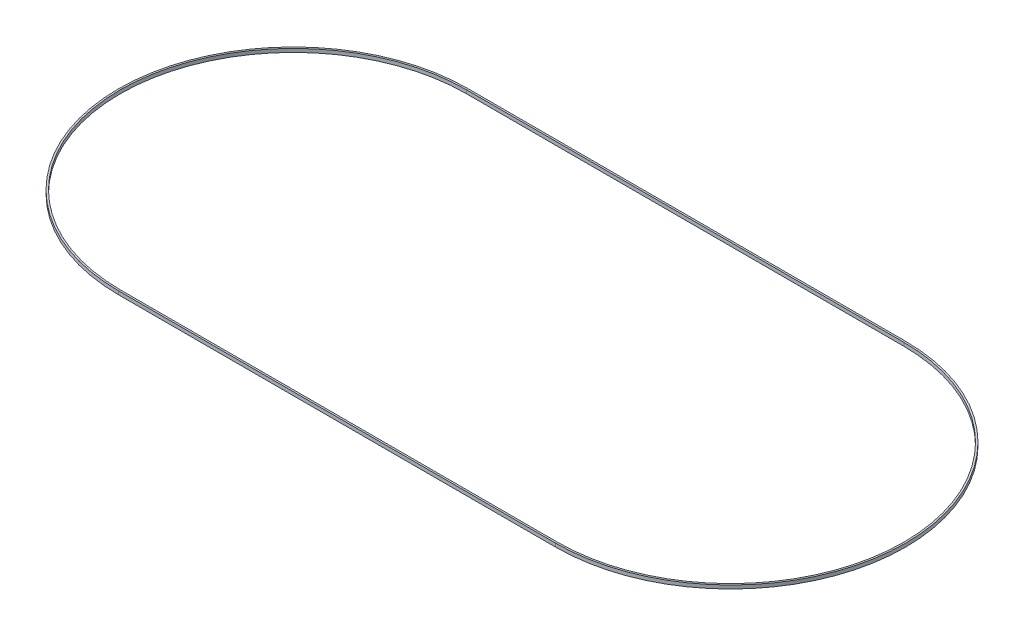
SolidWorks part; units mm, degrees
ref_plane "Front Plane" through (0, 0, 0) normal (0, 0, 1) x (1, 0, 0)
ref_plane "Top Plane" through (0, 0, 0) normal (0, 1, 0) x (1, 0, 0)
ref_plane "Right Plane" through (0, 0, 0) normal (1, 0, 0) x (0, 0, -1)
sketch "Sketch1" plane through (0, 0, 0) normal (0, 1, 0) x (1, 0, 0)
  line L0 (-25000, -20000) -> (25000, -20000)
  line L1 (-25000, 20000) -> (25000, 20000)
  line L2 (-25000, -20000) -> (-25000, 20000) construction
  line L3 (25000, -20000) -> (25000, 20000) construction
  line L4 (-25000, -19800) -> (25000, -19800)
  line L5 (-25000, 19800) -> (25000, 19800)
  arc A0 (-25000, 20000) -> (-25000, -20000) centre (-25000, 0) ccw
  arc A1 (25000, 20000) -> (25000, -20000) centre (25000, 0) cw
  arc A2 (25000, 19800) -> (25000, -19800) centre (25000, 0) cw
  arc A3 (-25000, 19800) -> (-25000, -19800) centre (-25000, 0) ccw
  dimension "D1" = 50000
  dimension "D2" = 40000
  dimension "D4" = 25000
  dimension "D5" = 200
  dimension "D3" = 0
extrude "Boss-Extrude1" add sketch "Sketch1" along normal blind 400 contours A1 L1 A0 L0 A3 L5 A2 L4
